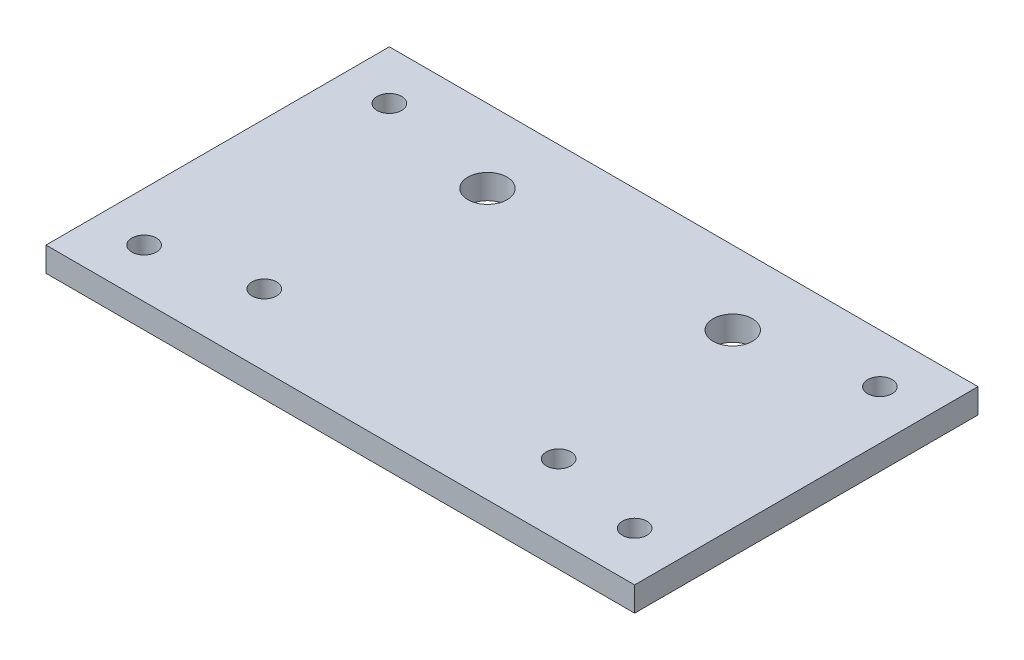
SolidWorks part; units mm, degrees
ref_plane "Front Plane" through (0, 0, 0) normal (0, 0, 1) x (1, 0, 0)
ref_plane "Top Plane" through (0, 0, 0) normal (0, 1, 0) x (1, 0, 0)
ref_plane "Right Plane" through (0, 0, 0) normal (1, 0, 0) x (0, 0, -1)
sketch "Sketch1" plane through (0, 0, 0) normal (0, 1, 0) x (1, 0, 0)
  line L1 (0, 2.946) -> (120, 2.946)
  line L2 (0, 2.946) -> (0, -67.054)
  line L3 (0, -67.054) -> (120, -67.054)
  line L4 (120, 2.946) -> (120, -67.054)
  circle A0 centre (35, -12.054) radius 4
  circle A1 centre (85, -12.054) radius 4
  circle A2 centre (10, -57.054) radius 2.5
  circle A3 centre (10, -7.054) radius 2.5
  circle A4 centre (30, -52.554) radius 2.5
  circle A5 centre (90, -52.554) radius 2.5
  circle A6 centre (110, -57.054) radius 2.5
  circle A7 centre (110, -7.054) radius 2.5
  dimension "D3" = 8
  dimension "D4" = 8
  dimension "D1" = 120
  dimension "D2" = 70
extrude "Boss-Extrude1" add sketch "Sketch1" along normal blind 5
